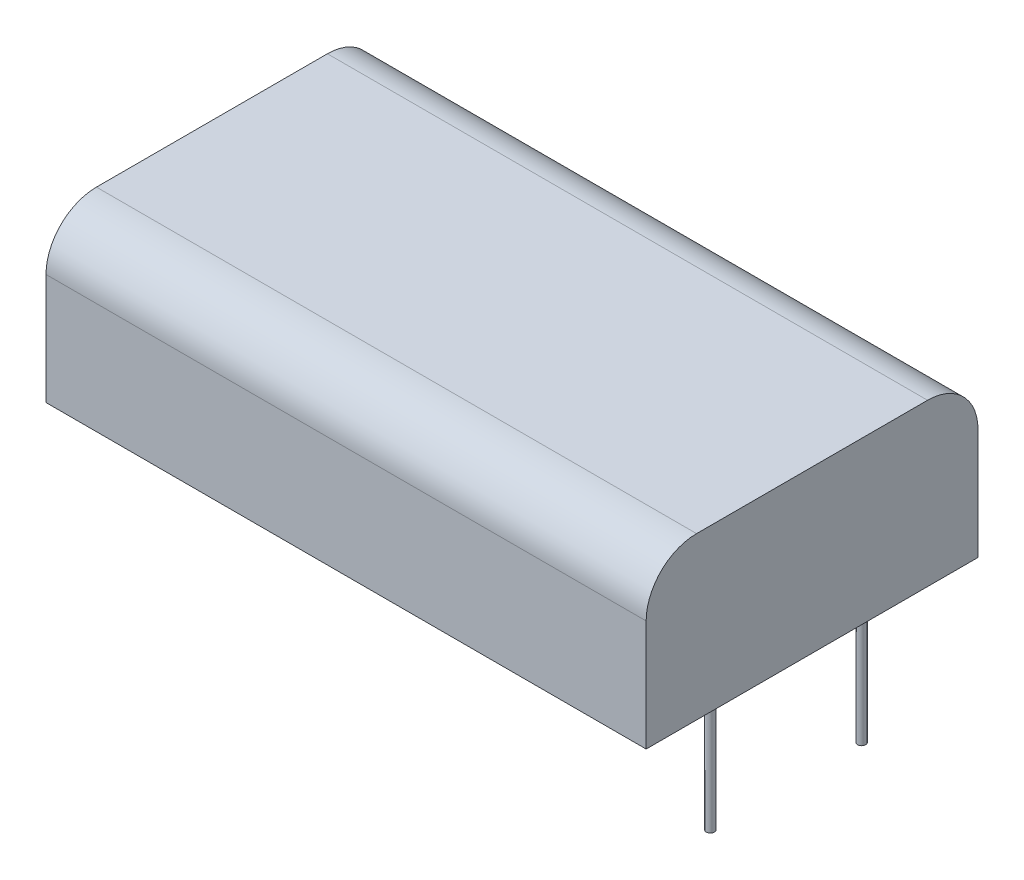
SolidWorks part; units mm, degrees
ref_plane "Front Plane" through (0, 0, 0) normal (0, 0, 1) x (1, 0, 0)
ref_plane "Top Plane" through (0, 0, 0) normal (0, 1, 0) x (1, 0, 0)
ref_plane "Right Plane" through (0, 0, 0) normal (1, 0, 0) x (0, 0, -1)
sketch "Sketch1" plane through (0, 0, 0) normal (0, 1, 0) x (1, 0, 0)
  line L1 (-29.75, -16.45) -> (29.75, -16.45)
  line L2 (-29.75, -16.45) -> (-29.75, 16.45)
  line L3 (-29.75, 16.45) -> (29.75, 16.45)
  line L4 (29.75, -16.45) -> (29.75, 16.45)
  line L5 (-29.75, -16.45) -> (29.75, 16.45) construction
  line L6 (-29.75, 16.45) -> (29.75, -16.45) construction
  point P0 (0, 0)
  dimension "D1" = 59.5
  dimension "D2" = 32.9
extrude "Boss-Extrude1" add sketch "Sketch1" along normal blind 16
fillet "Fillet1" radius 5 2 edges at (0, 16, -16.45) (0, 16, 16.45)
sketch "Sketch2" plane through (0, 0, 0) normal (0, -1, 0) x (1, 0, 0)
  line L0 (27.165, 7.5) -> (27.165, -7.5) construction
  line L1 (8.8, 0) -> (-8.8, 0) construction
  line L2 (0, -8.8) -> (0, 8.8) construction
  circle A0 centre (27.165, 7.5) radius 0.4
  circle A1 centre (27.165, -7.5) radius 0.4
  point P4 (27.165, 0)
  dimension "D1" = 0.8
  dimension "D2" = 15
  dimension "D3" = 27.165
extrude "Boss-Extrude2" add sketch "Sketch2" along normal blind 12.7
